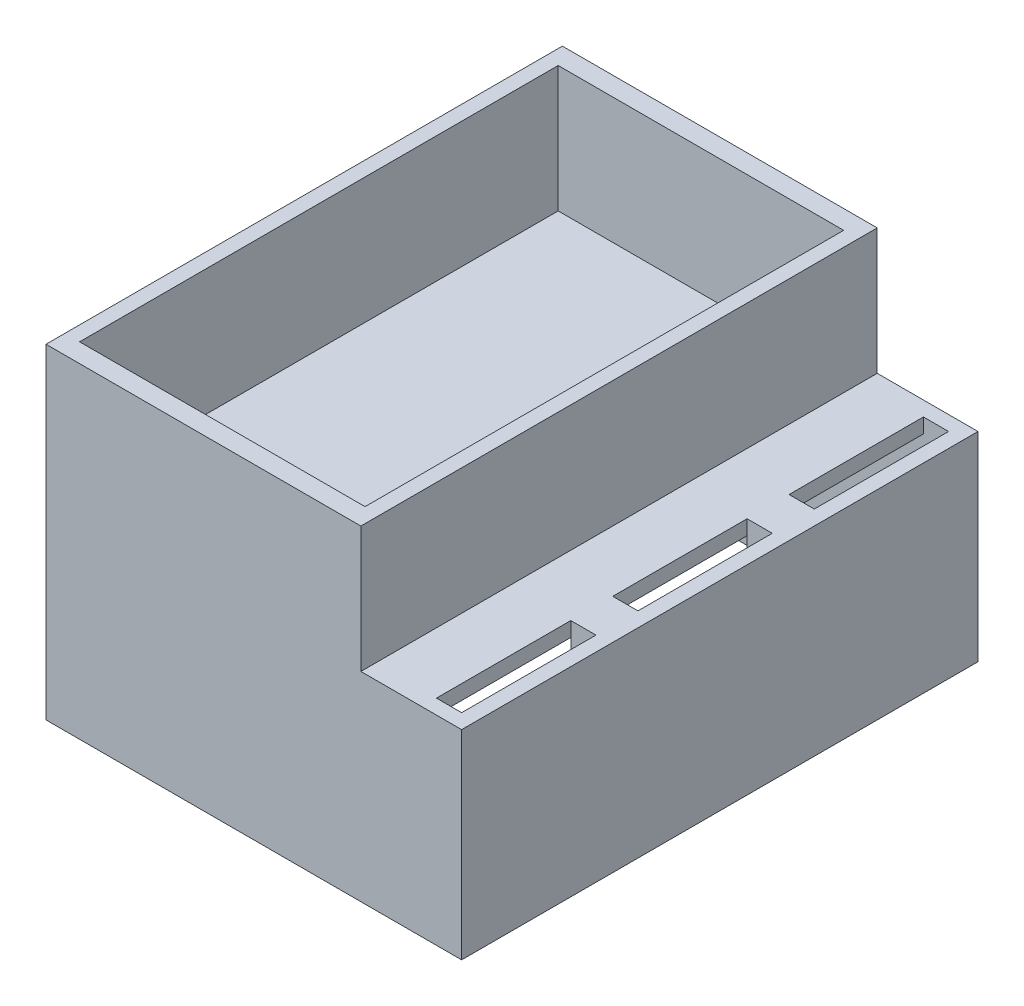
SolidWorks part; units mm, degrees
ref_plane "Front Plane" through (0, 0, 0) normal (0, 0, 1) x (1, 0, 0)
ref_plane "Top Plane" through (0, 0, 0) normal (0, 1, 0) x (1, 0, 0)
ref_plane "Right Plane" through (0, 0, 0) normal (1, 0, 0) x (0, 0, -1)
sketch "Sketch1" plane through (0, 0, 0) normal (0, 1, 0) x (1, 0, 0)
  line L1 (-138.162, -76.1412) -> (-88.662, -76.1412)
  line L2 (-138.162, -76.1412) -> (-138.162, -14.6412)
  line L3 (-138.162, -14.6412) -> (-88.662, -14.6412)
  line L4 (-88.662, -76.1412) -> (-88.662, -14.6412)
  dimension "D1" = 49.5
  dimension "D2" = 61.5
extrude "Boss-Extrude1" add sketch "Sketch1" along normal blind 23.75
sketch "Sketch2" plane through (0, 0, 0) normal (0, -1, 0) x (-1, 0, 0)
  line L0 (138.162, -76.1412) -> (88.662, -76.1412) construction
  line L1 (90.412, -74.3912) -> (136.412, -74.3912)
  line L2 (90.412, -74.3912) -> (90.412, -16.3912)
  line L3 (90.412, -16.3912) -> (136.412, -16.3912)
  line L4 (136.412, -74.3912) -> (136.412, -16.3912)
  line L5 (88.662, -76.1412) -> (88.662, -14.6412) construction
  line L6 (88.662, -14.6412) -> (138.162, -14.6412) construction
  line L7 (138.162, -14.6412) -> (138.162, -76.1412) construction
  dimension "D1" = 1.75
  dimension "D2" = 1.75
  dimension "D3" = 1.75
  dimension "D4" = 1.75
extrude "Cut-Extrude1" cut sketch "Sketch2" against normal blind 22
sketch "Sketch3" plane through (0, 22, 0) normal (0, -1, 0) x (-1, 0, 0)
  line L0 (136.412, -16.3912) -> (90.412, -16.3912) construction
  line L1 (90.412, -74.3912) -> (93.412, -74.3912)
  line L2 (90.412, -74.3912) -> (90.412, -16.3912)
  line L3 (90.412, -16.3912) -> (93.412, -16.3912)
  line L4 (93.412, -74.3912) -> (93.412, -16.3912)
  line L6 (90.412, -58.3912) -> (93.412, -58.3912)
  line L7 (90.412, -58.3912) -> (90.412, -53.3912)
  line L8 (90.412, -53.3912) -> (93.412, -53.3912)
  line L9 (93.412, -58.3912) -> (93.412, -53.3912)
  line L10 (90.412, -37.3912) -> (93.412, -37.3912)
  line L11 (90.412, -37.3912) -> (90.412, -32.3912)
  line L12 (90.412, -32.3912) -> (93.412, -32.3912)
  line L13 (93.412, -37.3912) -> (93.412, -32.3912)
  line M9 (90.412, -16.3912) -> (90.412, -74.3912)
  line M10 (90.412, -74.3912) -> (136.412, -74.3912)
  line M12 (136.412, -16.3912) -> (90.412, -16.3912)
  dimension "D1" = 3
  dimension "D2" = 5
  dimension "D3" = 5
  dimension "D4" = 16
  dimension "D5" = 16
extrude "Cut-Extrude2" cut sketch "Sketch3" against normal blind 1.75 contours L6 L2 L4 M10 | L12 L4 M9 M12 | L10 L2 L8 L4
sketch "Sketch7" plane through (0, 22, 0) normal (0, -1, 0) x (-1, 0, 0)
  line L1 (90.412, -58.3912) -> (93.412, -58.3912)
  line L2 (90.412, -58.3912) -> (90.412, -53.3912)
  line L3 (90.412, -53.3912) -> (93.412, -53.3912)
  line L4 (93.412, -58.3912) -> (93.412, -53.3912)
  line L5 (90.412, -37.3912) -> (93.412, -37.3912)
  line L6 (90.412, -37.3912) -> (90.412, -32.3912)
  line L7 (90.412, -32.3912) -> (93.412, -32.3912)
  line L8 (93.412, -37.3912) -> (93.412, -32.3912)
  point P10 (91.4714, -46.0867)
extrude "Boss-Extrude2" add sketch "Sketch7" along normal blind 4 contours L2 L1 L4 L3 | L6 L5 L8 L7
sketch "Sketch9" plane through (-93.412, 0, 0) normal (-1, 0, 0) x (0, 0, 1)
  line L0 (58.3912, 18) -> (58.3912, 22) construction
  line L1 (58.3912, 20.407) -> (53.3912, 20.407)
  line L2 (58.3912, 20.407) -> (58.3912, 22)
  line L3 (58.3912, 22) -> (53.3912, 22)
  line L4 (53.3912, 20.407) -> (53.3912, 22)
  point P7 (52.9928, 22.2027)
sketch "Sketch11" plane through (0, 23.75, 0) normal (0, 1, 0) x (1, 0, 0)
  line L0 (-138.162, -76.1412) -> (-88.662, -76.1412) construction
  line L1 (-138.162, -14.6412) -> (-100.662, -14.6412)
  line L2 (-138.162, -14.6412) -> (-138.162, -76.1412)
  line L3 (-138.162, -76.1412) -> (-100.662, -76.1412)
  line L4 (-100.662, -14.6412) -> (-100.662, -76.1412)
  dimension "D1" = 37.5
extrude "Boss-Extrude3" add sketch "Sketch11" along normal blind 15
sketch "Sketch12" plane through (0, 38.75, 0) normal (0, 1, 0) x (1, 0, 0)
  line L0 (-138.162, -14.6412) -> (-138.162, -76.1412) construction
  line L1 (-136.412, -16.8912) -> (-102.412, -16.8912)
  line L2 (-136.412, -16.8912) -> (-136.412, -73.8912)
  line L3 (-136.412, -73.8912) -> (-102.412, -73.8912)
  line L4 (-102.412, -16.8912) -> (-102.412, -73.8912)
  line L5 (-100.662, -76.1412) -> (-100.662, -14.6412) construction
  line L6 (-100.662, -14.6412) -> (-138.162, -14.6412) construction
  line L7 (-138.162, -76.1412) -> (-100.662, -76.1412) construction
  dimension "D1" = 1.75
  dimension "D2" = 1.75
  dimension "D3" = 2.25
  dimension "D4" = 2.25
extrude "Cut-Extrude3" cut sketch "Sketch12" against normal blind 15
